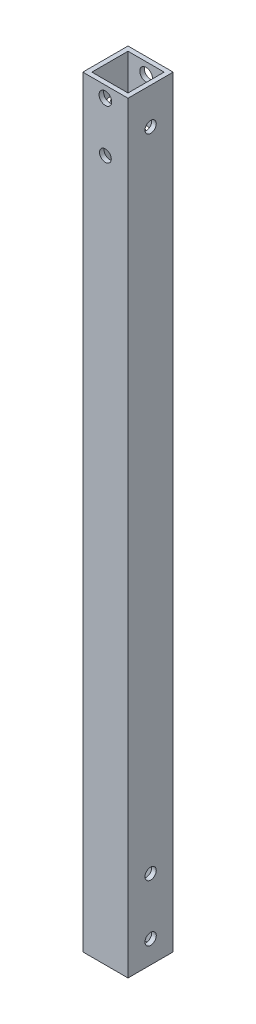
SolidWorks part; units mm, degrees
material "Gerais  - 6061-T6"
ref_plane "Plano frontal" through (0, 0, 0) normal (0, 0, 1) x (1, 0, 0)
ref_plane "Plano superior" through (0, 0, 0) normal (0, 1, 0) x (1, 0, 0)
ref_plane "Plano direito" through (0, 0, 0) normal (1, 0, 0) x (0, 0, -1)
sketch "Esboço1" plane through (0, 0, 0) normal (0, 1, 0) x (1, 0, 0)
  line L1 (0, 0) -> (20, 0)
  line L2 (0, 0) -> (0, 20)
  line L3 (0, 20) -> (20, 20)
  line L4 (20, 0) -> (20, 20)
  dimension "D1" = 20
extrude "Extrusão-Fina1" add sketch "Esboço1" along normal blind 337 thin thin type one direction reverse wall 2
sketch "Esboço2" plane through (0, 0, 0) normal (-1, 0, 0) x (0, 0, 1)
  circle A0 centre (-10, 35) radius 2.5
  circle A1 centre (-10, 10) radius 2.5
extrude "Corte-extrusão1" cut sketch "Esboço2" against normal through all
sketch "Esboço3" plane through (0, 0, -20) normal (0, 0, -1) x (-1, 0, 0)
  circle A2 centre (-10, 310) radius 2.6
  circle A3 centre (-10, 332) radius 2.8
extrude "Corte-extrusão2" cut sketch "Esboço3" against normal through all
sketch "Esboço4" plane through (20, 0, 0) normal (1, 0, 0) x (0, 0, -1)
  line L0 (0, 337) -> (20, 337) construction
  circle A0 centre (10, 321) radius 2.5
  point P2 (0, 0)
  point P3 (10, 337)
  dimension "D1" = 5
  dimension "D2" = 16
extrude "Corte-extrusão3" cut sketch "Esboço4" against normal through all
